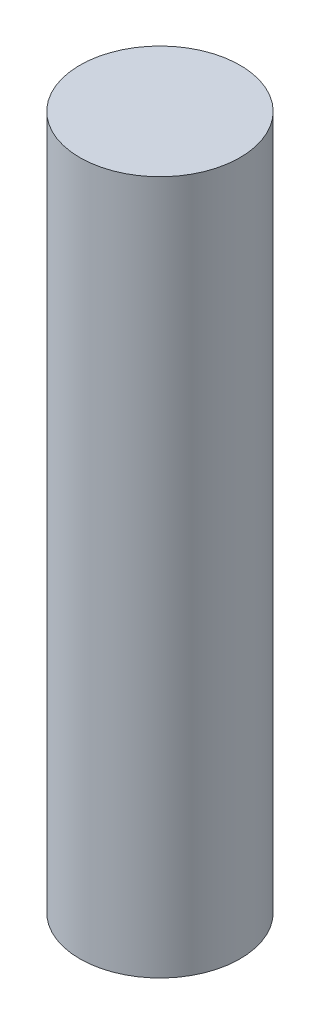
SolidWorks part; units mm, degrees
ref_plane "Front Plane" through (0, 0, 0) normal (0, 0, 1) x (1, 0, 0)
ref_plane "Top Plane" through (0, 0, 0) normal (0, 1, 0) x (1, 0, 0)
ref_plane "Right Plane" through (0, 0, 0) normal (1, 0, 0) x (0, 0, -1)
sketch "Sketch1" plane through (0, 0, 0) normal (0, 1, 0) x (1, 0, 0)
  circle A0 centre (0, 0) radius 0.3969
  dimension "D1" = 0.7937
extrude "Boss-Extrude1" add sketch "Sketch1" along normal blind 3.4392 contours A0
